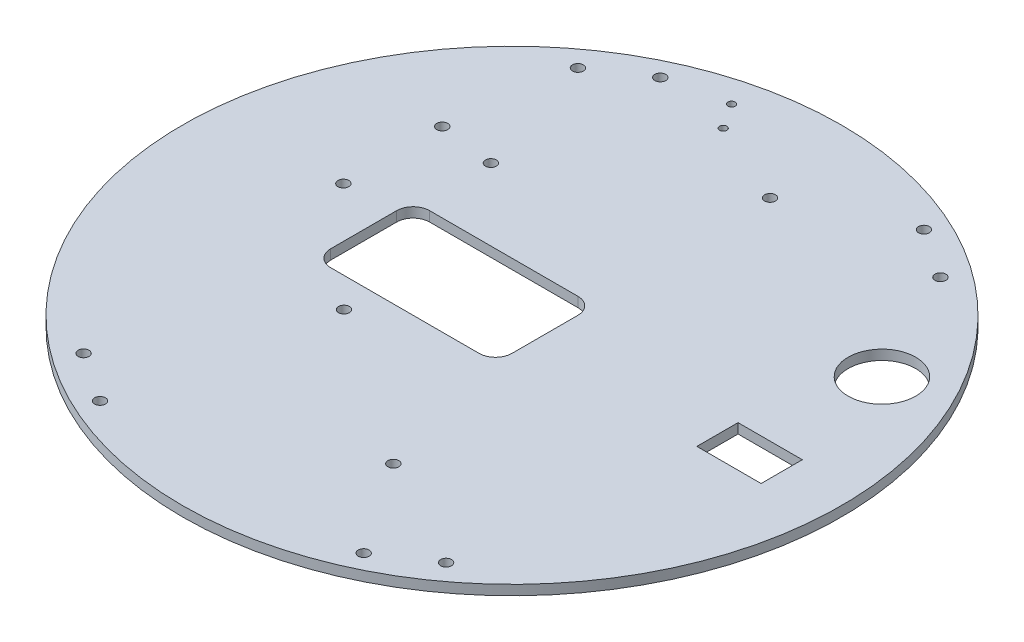
SolidWorks part; units mm, degrees
ref_plane "Alzado" through (0, 0, 0) normal (0, 0, 1) x (1, 0, 0)
ref_plane "Planta" through (0, 0, 0) normal (0, 1, 0) x (1, 0, 0)
ref_plane "Vista lateral" through (0, 0, 0) normal (1, 0, 0) x (0, 0, -1)
sketch "Croquis1" plane through (0, 0, 0) normal (0, 1, 0) x (1, 0, 0)
  line L0 (0, 66) -> (0, -71.35) construction
  line L5 (0, 0) -> (30.8, 0) construction
  line L27 (-80.2024, 58.028) -> (-63.2024, 58.028) construction
  line L28 (-80.2024, 58.028) -> (-80.2024, -9.972) construction
  line L29 (-80.2024, -9.972) -> (-63.2024, -9.972) construction
  line L30 (-63.2024, 58.028) -> (-63.2024, -9.972) construction
  line L32 (-80.2024, -9.972) -> (-72.2024, -9.972) construction
  line L33 (-80.2024, -9.972) -> (-80.2024, -54.972) construction
  line L34 (-80.2024, -54.972) -> (-72.2024, -54.972) construction
  line L35 (-72.2024, -9.972) -> (-72.2024, -54.972) construction
  line L37 (-40, 15) -> (5, 15)
  line L38 (-45, 10) -> (-45, -10)
  line L39 (-40, -15) -> (5, -15)
  line L40 (10, 10) -> (10, -10)
  line L42 (62.5, 6.0915) -> (82, 6.0915)
  line L43 (62.5, 6.0915) -> (62.5, -6.4085)
  line L44 (62.5, -6.4085) -> (82, -6.4085)
  line L45 (82, 6.0915) -> (82, -6.4085)
  circle A6 centre (55, 75) radius 1.65
  circle A15 centre (40, -85) radius 1.65
  circle A16 centre (40, 85) radius 1.65
  circle A19 centre (0, 0) radius 100
  circle A20 centre (-60.2024, 39.028) radius 1.65
  circle A25 centre (-40, -85) radius 1.65
  circle A26 centre (-55, -75) radius 1.65
  circle A27 centre (-55, 75) radius 1.65
  circle A28 centre (-40, 85) radius 1.65
  circle A29 centre (-60.2024, 9.028) radius 1.65
  circle A30 centre (72.25, 40) radius 10.25
  circle A33 centre (-43.2024, 36.8) radius 1.65
  circle A34 centre (8.2976, 70) radius 1.65
  circle A35 centre (-43.2024, 70) radius 1.65 construction
  circle A36 centre (21, -57) radius 1.65
  circle A37 centre (-27, -24) radius 1.65
  arc A38 (5, 15) -> (10, 10) centre (5, 10) cw
  arc A39 (5, -15) -> (10, -10) centre (5, -10) ccw
  arc A40 (-45, -10) -> (-40, -15) centre (-40, -10) ccw
  arc A41 (-40, 15) -> (-45, 10) centre (-40, 10) ccw
  circle A42 centre (55, -75) radius 1.65
  circle A43 centre (-22.1824, 88.81) radius 1.1
  circle A44 centre (-17.1024, 81.19) radius 1.1
  point P17 (0, 0)
  point P57 (10, 0)
  point P67 (72.25, 6.0915)
  point P72 (0, 0)
  dimension "D10" = 200
  dimension "D14" = 3.3
  dimension "D3" = 68
  dimension "D7" = 3.3
  dimension "D27" = 30
  dimension "D28" = 55
  dimension "D13" = 30
  dimension "D16" = 3.3
  dimension "D2" = 20.5
  dimension "D18" = 13
  dimension "D24" = 61
  dimension "D26" = 5
  dimension "D32" = 5.08
  dimension "D34" = 2.2
  dimension "D4" = 17
  dimension "D5" = 75
  dimension "D6" = 55
  dimension "D8" = 40
  dimension "D9" = 85
  dimension "D11" = 45
  dimension "D12" = 8
  dimension "D15" = 19
  dimension "D17" = 3
  dimension "D19" = 48
  dimension "D20" = 51.5
  dimension "D21" = 33.2
  dimension "D22" = 5
  dimension "D23" = 17
  dimension "D25" = 33
  dimension "D29" = 10
  dimension "D30" = 35
  dimension "D31" = 17.25
  dimension "D33" = 7.62
  dimension "D35" = 25.4
  dimension "D36" = 3.81
  dimension "D37" = 19.5
  dimension "D38" = 12.5
extrude "Saliente-Extruir1" add sketch "Croquis1" along normal blind 3
